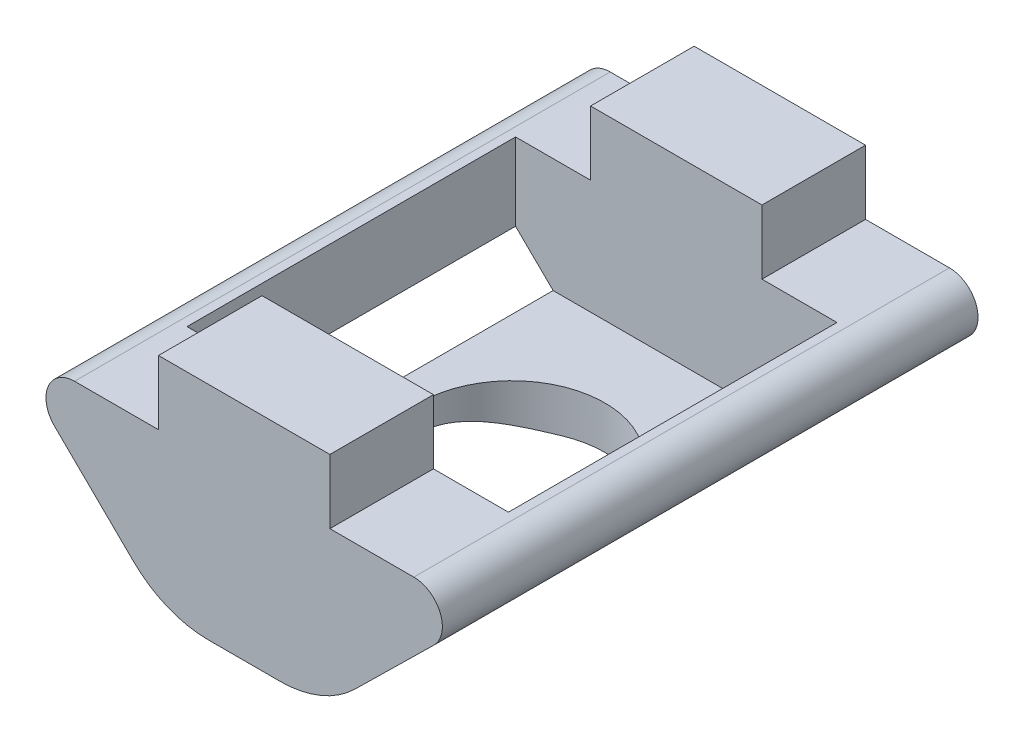
SolidWorks part; units mm, degrees
ref_plane "前视基准面" through (0, 0, 0) normal (0, 0, 1) x (1, 0, 0)
ref_plane "上视基准面" through (0, 0, 0) normal (0, 1, 0) x (1, 0, 0)
ref_plane "右视基准面" through (0, 0, 0) normal (1, 0, 0) x (0, 0, -1)
sketch "Sketch1" plane through (0, 0, 0) normal (0, 0, 1) x (1, 0, 0)
  line L0 (-4.75, 1.3) -> (-2.4, 1.3)
  line L1 (-2.4, 1.3) -> (-2.4, 3.1)
  line L2 (-2.4, 3.1) -> (2.4, 3.1)
  line L3 (-5.3106, -0.0707) -> (-3.1024, -2.2401)
  line L4 (-1, -3.1) -> (1, -3.1)
  line L5 (0, 3.1) -> (0, -3.1) construction
  line L6 (5.3106, -0.0707) -> (3.1024, -2.2401)
  line L7 (4.75, 1.3) -> (2.4, 1.3)
  line L8 (2.4, 1.3) -> (2.4, 3.1)
  arc A0 (-5.3106, -0.0707) -> (-4.75, 1.3) centre (-4.75, 0.5) cw
  arc A1 (-1, -3.1) -> (-3.1024, -2.2401) centre (-1, -0.1) cw
  arc A2 (1, -3.1) -> (3.1024, -2.2401) centre (1, -0.1) ccw
  arc A3 (5.3106, -0.0707) -> (4.75, 1.3) centre (4.75, 0.5) ccw
  dimension "D2" = 0.8
  dimension "D3" = 3
  dimension "D1" = 2.4
  dimension "D4" = 4.75
  dimension "D5" = 1
  dimension "D6" = 1.8
  dimension "D7" = 6.2
extrude "Boss-Extrude1" add sketch "Sketch1" along normal blind 15
sketch "Sketch2" plane through (0, 3.1, 0) normal (0, 1, 0) x (1, 0, 0)
  line L0 (0, -15) -> (0, 0) construction
  line L1 (2.4, -15) -> (-2.4, -15) construction
  line L2 (2.4, 0) -> (-2.4, 0) construction
  circle A0 centre (0, -7.5) radius 2.6
  dimension "D1" = 5.2
extrude "Cut-Extrude1" cut sketch "Sketch2" against normal through all
sketch "Sketch5" plane through (0, 1.3, 0) normal (0, 1, 0) x (1, 0, 0)
  arc A0 (-2.4, -6.5) -> (-2.4, -8.5) centre (0, -7.5) ccw construction
  point P0 (-2.6, -7.5)
ref_plane "Plane1" through (0, 0, 7.5) normal (0, 0, 1) x (1, 0, 0)
sketch "Sketch6" plane through (0, 0, 7.5) normal (0, 0, 1) x (1, 0, 0)
  line L0 (-4.5, -1.9) -> (-4.5, 1.3)
  line L1 (-4.5, 1.3) -> (4.5, 1.3)
  line L2 (4.5, 1.3) -> (4.5, -1.9)
  line L4 (-4.5, -1.9) -> (4.5, -1.9)
  line L6 (0, 1.3) -> (0, -1.9) construction
  line L7 (2.4, 3.1) -> (-2.4, 3.1) construction
  line L8 (-2.4, 1.3) -> (-4.75, 1.3) construction
  point P2 (0, -1.9)
  point P7 (0, 1.3)
  point P10 (0, 3.1)
  dimension "D1" = 9
  dimension "D2" = 3.2
extrude "Cut-Extrude2" cut sketch "Sketch6" against normal blind 4.6 and the other way blind 4.6
sketch "Sketch7" plane through (0, 1.3, 0) normal (0, 1, 0) x (1, 0, 0)
  line L1 (4.5, -2.9) -> (-4.5, -2.9)
  line L2 (4.5, -2.9) -> (4.5, -12.1)
  line L3 (4.5, -12.1) -> (-4.5, -12.1)
  line L4 (-4.5, -2.9) -> (-4.5, -12.1)
extrude "Cut-Extrude3" cut sketch "Sketch7" along normal through all
